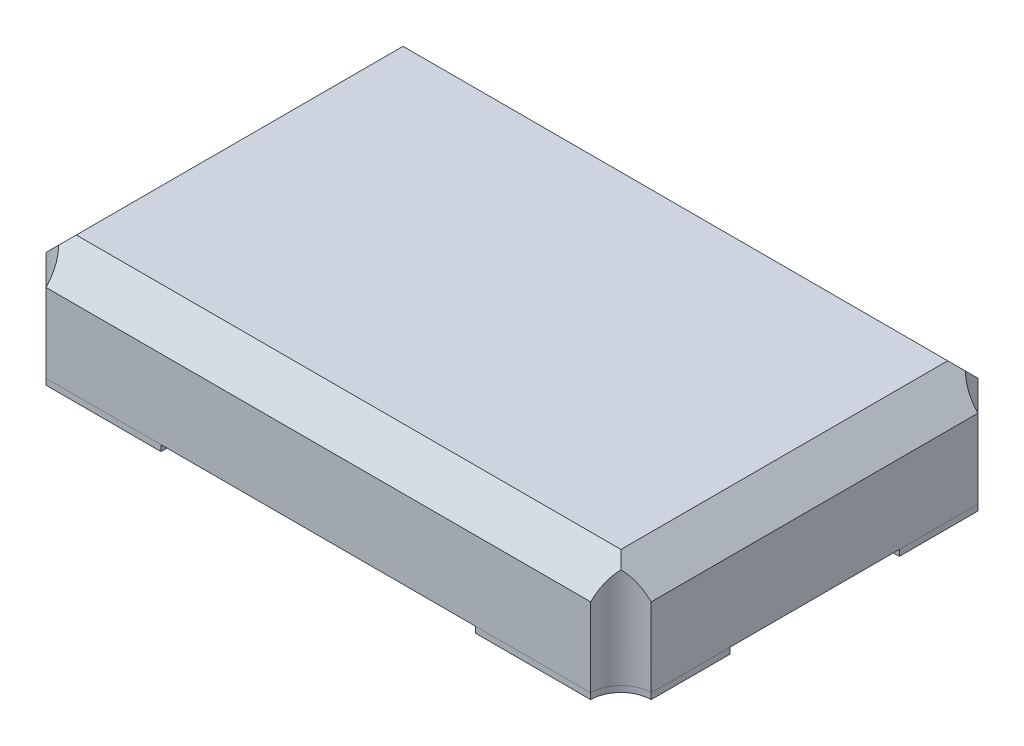
SolidWorks part; units mm, degrees
ref_plane "Front Plane" through (0, 0, 0) normal (0, 0, 1) x (1, 0, 0)
ref_plane "Top Plane" through (0, 0, 0) normal (0, 1, 0) x (1, 0, 0)
ref_plane "Right Plane" through (0, 0, 0) normal (1, 0, 0) x (0, 0, -1)
sketch "Sketch1" plane through (0, 0, 0) normal (0, 1, 0) x (1, 0, 0)
  line L1 (-42.1832, -32.4269) -> (-37.1832, -32.4269)
  line L2 (-42.1832, -32.4269) -> (-42.1832, -35.6269)
  line L3 (-42.1832, -35.6269) -> (-37.1832, -35.6269)
  line L4 (-37.1832, -32.4269) -> (-37.1832, -35.6269)
  dimension "D1" = 3.2
  dimension "D2" = 5
extrude "Extrude1" add sketch "Sketch1" along normal blind 0.9
chamfer "Chamfer1" distance 0.25 angle 45 4 edges at (-37.1832, 0.9, 34.0269) (-39.6832, 0.9, 35.6269) (-42.1832, 0.9, 34.0269) (-39.6832, 0.9, 32.4269)
sketch "Sketch2" plane through (0, 0, 0) normal (0, -1, 0) x (1, 0, 0)
  line L1 (-42.1832, 35.6269) -> (-40.9832, 35.6269)
  line L2 (-42.1832, 35.6269) -> (-42.1832, 34.7269)
  line L3 (-42.1832, 34.7269) -> (-40.9832, 34.7269)
  line L4 (-40.9832, 35.6269) -> (-40.9832, 34.7269)
  line L5 (-37.1832, 35.6269) -> (-38.3832, 35.6269)
  line L6 (-37.1832, 35.6269) -> (-37.1832, 34.7269)
  line L7 (-37.1832, 34.7269) -> (-38.3832, 34.7269)
  line L8 (-38.3832, 35.6269) -> (-38.3832, 34.7269)
  line L9 (-37.1832, 32.4269) -> (-38.3832, 32.4269)
  line L10 (-37.1832, 32.4269) -> (-37.1832, 33.3269)
  line L11 (-37.1832, 33.3269) -> (-38.3832, 33.3269)
  line L12 (-38.3832, 32.4269) -> (-38.3832, 33.3269)
  line L13 (-42.1832, 32.4269) -> (-40.9832, 32.4269)
  line L14 (-42.1832, 32.4269) -> (-42.1832, 33.3269)
  line L15 (-42.1832, 33.3269) -> (-40.9832, 33.3269)
  line L16 (-40.9832, 32.4269) -> (-40.9832, 33.3269)
  dimension "D1" = 0.9
  dimension "D2" = 1.2
  dimension "D3" = 1.2
  dimension "D4" = 0.9
  dimension "D5" = 0.9
extrude "Extrude2" add sketch "Sketch2" along normal blind 0.05 separate body
sketch "Sketch3" plane through (0, 0.9, 0) normal (0, 1, 0) x (1, 0, 0)
  circle A0 centre (-42.1832, -32.4269) radius 0.25
  circle A1 centre (-37.1832, -32.4269) radius 0.25
  circle A2 centre (-37.1832, -35.6269) radius 0.25
  circle A3 centre (-42.1832, -35.6269) radius 0.25
  dimension "D1" = 0.5
  dimension "D2" = 0.5
  dimension "D3" = 0.5
  dimension "D4" = 0.5
extrude "Extrude3" cut sketch "Sketch3" against normal through all
